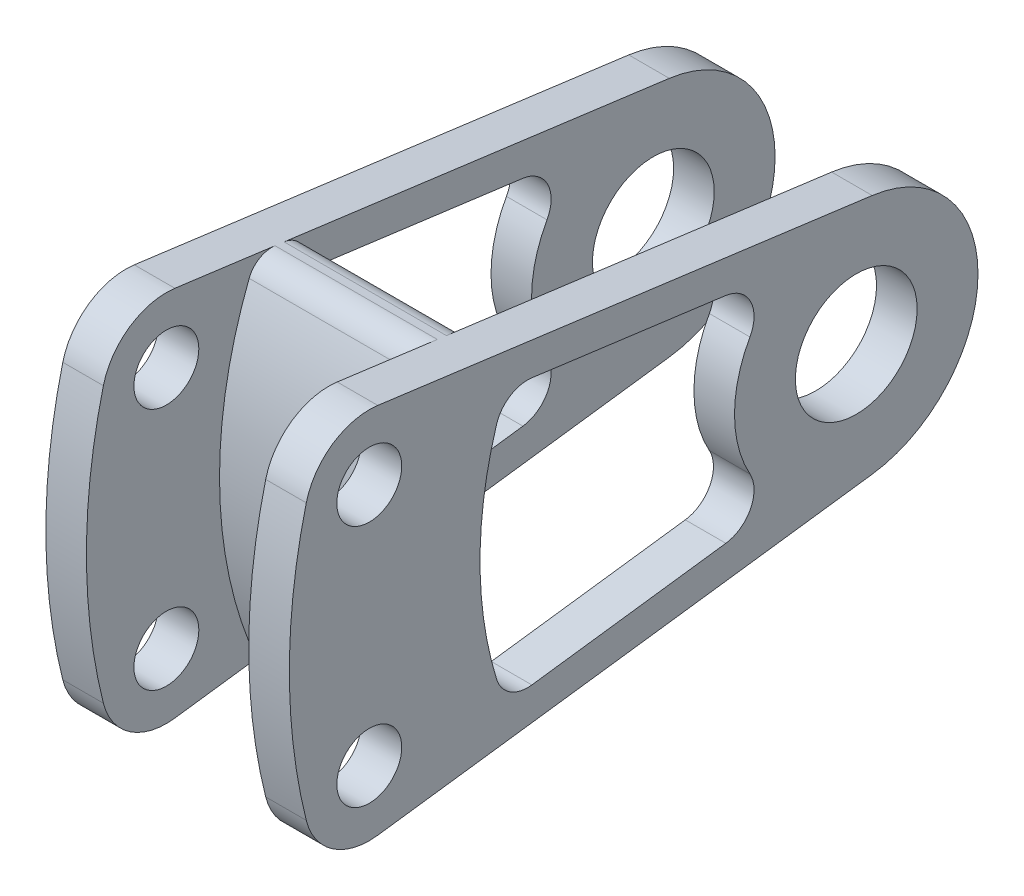
SolidWorks part; units mm, degrees
material "7075-O (SS)"
ref_plane "Front Plane" through (0, 0, 0) normal (0, 0, 1) x (1, 0, 0)
ref_plane "Top Plane" through (0, 0, 0) normal (0, 1, 0) x (1, 0, 0)
ref_plane "Right Plane" through (0, 0, 0) normal (1, 0, 0) x (0, 0, -1)
sketch3d "3DSketch1"
  line L0 (1165, -215, 403) -> (1165, -245, 403)
  line L1 (1155, -230, 343) -> (1165, -215, 403)
  line L2 (1165, -215, 403) -> (1175, -230, 343)
  line L3 (1175, -230, 343) -> (1165, -245, 403)
  line L4 (1165, -245, 403) -> (1155, -230, 343)
  line L5 (1155, -230, 343) -> (1175, -230, 343)
  line L6 (1165, -245, 403) -> (1165, -230, 343)
  point P0 (1165, -245, 403)
  point P1 (1175, -230, 343)
  point P2 (1165, -215, 403)
  point P3 (1155, -230, 343)
  point P7 (0, 0, 0)
  point P8 (0, 0, 0)
  point P11 (0, 0, 0)
  point P12 (0, 0, 0)
ref_plane "Plane4" through (1165, 0, 0) normal (1, 0, 0) x (0, 0, -1)
sketch "Sketch1" plane through (1165, 0, 0) normal (1, 0, 0) x (0, 0, -1)
  line L4 (-401.9506, -207.0691) -> (-343, -214.8693)
  line L5 (-401.9506, -252.9309) -> (-341.0324, -244.8704)
  line L7 (-401.9506, -207.0691) -> (-341.0324, -215.1296)
  circle A0 centre (-343, -230) radius 7.5
  circle A1 centre (-403, -215) radius 4
  circle A2 centre (-403, -245) radius 4
  arc A3 (-401.9506, -207.0691) -> (-410.7611, -213.0597) centre (-403, -215) ccw
  arc A4 (-410.7611, -246.9403) -> (-401.9506, -252.9309) centre (-403, -245) ccw
  arc A5 (-341.0324, -244.8704) -> (-341.0324, -215.1296) centre (-343, -230) ccw
  arc A6 (-410.7611, -213.0597) -> (-410.7611, -246.9403) centre (-343, -230) ccw
  dimension "D1" = 16
  dimension "D2" = 8
  dimension "D3" = 8
  dimension "D4" = 16
  dimension "D5" = 15
  dimension "D6" = 30
extrude "Boss-Extrude2" add sketch "Sketch1" along normal mid plane 30
sketch "Sketch3" plane through (1150, 0, 0) normal (-1, 0, 0) x (0, 0, 1)
  line L0 (401.9506, -252.9309) -> (341.0324, -244.8704) construction
  line L1 (401.9506, -207.0691) -> (341.0324, -215.1296) construction
  line L2 (388.6861, -208.8242) -> (341.0324, -215.1296)
  line L3 (388.6861, -251.1758) -> (341.0324, -244.8704)
  line L7 (386.199, -213.1882) -> (356.9152, -217.0629)
  line L8 (386.199, -246.8118) -> (356.9152, -242.9371)
  line L9 (356.9152, -217.0629) -> (351.667, -217.7573)
  line L10 (356.9152, -242.9371) -> (351.667, -242.2427)
  arc A1 (351.667, -242.2427) -> (351.667, -217.7573) centre (343, -230) ccw
  circle A2 centre (403, -215) radius 8
  circle A3 centre (403, -245) radius 8
  arc A8 (386.199, -246.8118) -> (386.199, -213.1882) centre (343, -230) ccw
  arc A10 (356.9152, -242.9371) -> (356.9152, -217.0629) centre (343, -230) ccw construction
  arc A12 (341.0324, -244.8704) -> (341.0324, -215.1296) centre (343, -230) ccw construction
  arc A13 (388.6861, -251.1758) -> (388.6861, -208.8242) centre (343, -230) ccw construction
  dimension "D1" = 16
  dimension "D2" = 16
  dimension "D3" = 4
extrude "Cut-Extrude3" cut sketch "Sketch3" against normal through all contours L8 A8 L7 L9 A1 L10
fillet "Fillet1" radius 4 4 edges at (1165, -213.1882, 386.199) (1165, -217.7573, 351.667) (1165, -242.2427, 351.667) (1165, -246.8118, 386.199)
sketch "Sketch14" plane through (1165, 0, 0) normal (1, 0, 0) x (0, 0, -1)
  line L0 (-374.4762, -186.8017) -> (-394.6287, -182.9572)
  line L1 (-380.9384, -267.65) -> (-393.2247, -278.5389)
  arc A0 (-394.6287, -182.9572) -> (-393.2247, -278.5389) centre (-343, -230) ccw
  arc A1 (-374.4762, -186.8017) -> (-380.9384, -267.65) centre (-343, -230) ccw
extrude "Cut-Extrude8" cut sketch "Sketch14" against normal mid plane 20
sketch "Sketch16" plane through (1165, 0, 0) normal (1, 0, 0) x (0, 0, -1)
  circle A2 centre (-343, -230) radius 46.3551
extrude "Cut-Extrude9" cut sketch "Sketch16" against normal mid plane 20
fillet "Fillet6" radius 3 2 edges at (1165, -208.4002, 391.8906) (1165, -251.5998, 391.8906)
fillet "Fillet7" radius 3 2 edges at (1165, -209.3762, 384.5145) (1165, -250.6238, 384.5145)
